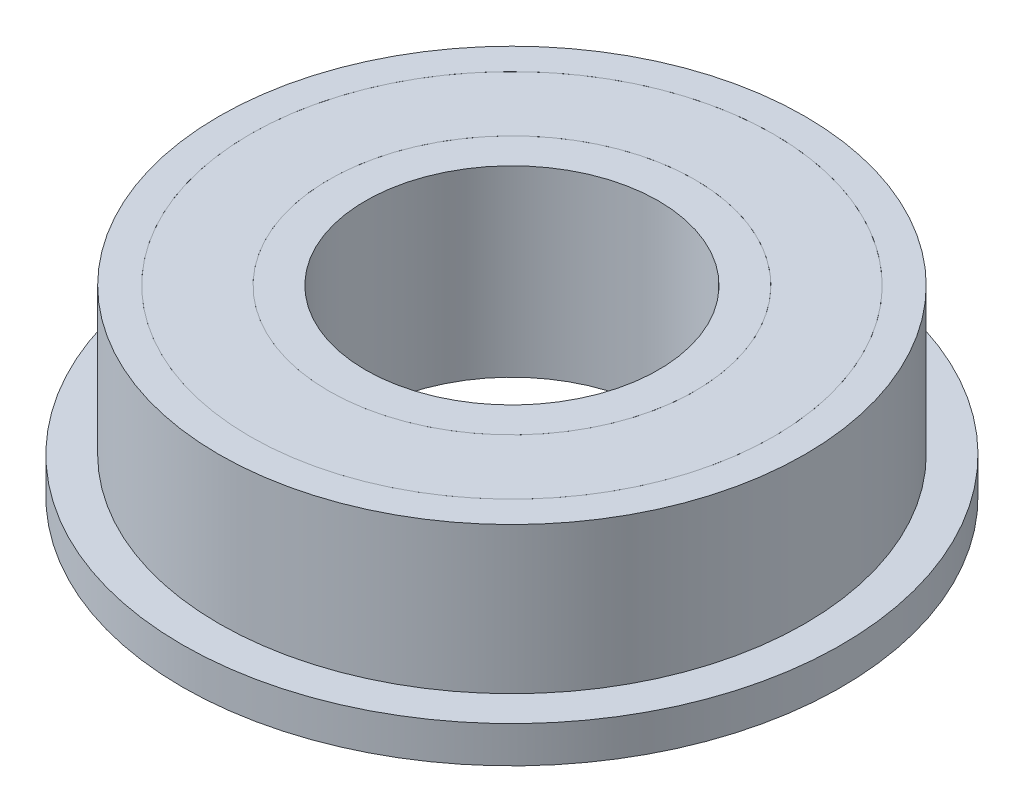
SolidWorks part; units mm, degrees
ref_plane "Front Plane" through (0, 0, 0) normal (0, 0, 1) x (1, 0, 0)
ref_plane "Top Plane" through (0, 0, 0) normal (0, 1, 0) x (1, 0, 0)
ref_plane "Right Plane" through (0, 0, 0) normal (1, 0, 0) x (0, 0, -1)
sketch "Sketch1" plane through (0, 0, 0) normal (0, 1, 0) x (1, 0, 0)
  circle A0 centre (0, 0) radius 9
  dimension "D1" = 18
extrude "Boss-Extrude1" add sketch "Sketch1" along normal blind 1
sketch "Sketch2" plane through (0, 1, 0) normal (0, 1, 0) x (1, 0, 0)
  circle A0 centre (0, 0) radius 8
  dimension "D1" = 16
extrude "Boss-Extrude2" add sketch "Sketch2" along normal blind 4
sketch "Sketch3" plane through (0, 5, 0) normal (0, 1, 0) x (1, 0, 0)
  circle A0 centre (0, 0) radius 7.15
  dimension "D1" = 14.3
extrude "Cut-Extrude1" cut sketch "Sketch3" against normal blind 14
sketch "Sketch4" plane through (0, 0, 0) normal (0, -1, 0) x (1, 0, 0)
  circle A0 centre (0, 0) radius 7.15
extrude "Boss-Extrude3" add sketch "Sketch4" against normal up to surface (5 mm away) separate body up to face at (0, 5, 7.15)
sketch "Sketch5" plane through (0, 5, 0) normal (0, 1, 0) x (1, 0, 0)
  circle A0 centre (0, 0) radius 5
  dimension "D1" = 10
extrude "Cut-Extrude2" cut sketch "Sketch5" against normal blind 14
sketch "Sketch6" plane through (0, 0, 0) normal (0, -1, 0) x (1, 0, 0)
  circle A0 centre (0, 0) radius 5
extrude "Boss-Extrude4" add sketch "Sketch6" against normal up to surface (5 mm away) separate body up to face at (0, 5, 5)
sketch "Sketch7" plane through (0, 5, 0) normal (0, 1, 0) x (1, 0, 0)
  circle A0 centre (0, 0) radius 4
  dimension "D1" = 8
extrude "Cut-Extrude3" cut sketch "Sketch7" against normal blind 14
